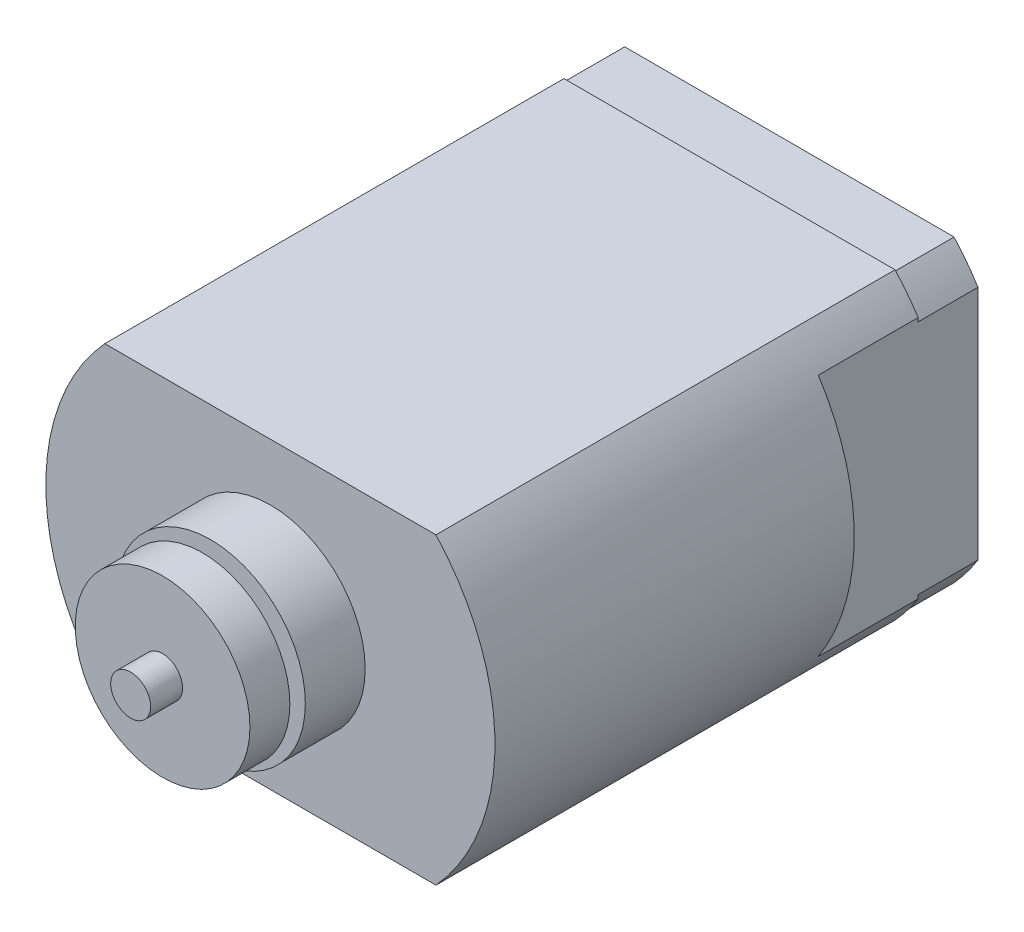
SolidWorks part; units mm, degrees
ref_plane "前视基准面" through (0, 0, 0) normal (0, 0, 1) x (1, 0, 0)
ref_plane "上视基准面" through (0, 0, 0) normal (0, 1, 0) x (1, 0, 0)
ref_plane "右视基准面" through (0, 0, 0) normal (1, 0, 0) x (0, 0, -1)
sketch "草图1" plane through (0, 0, 0) normal (0, 0, 1) x (1, 0, 0)
  line L0 (-11.25, 0) -> (11.25, 0) construction
  line L1 (-8.2947, 7.6) -> (8.2947, 7.6)
  line L2 (-8.2947, -7.6) -> (8.2947, -7.6)
  arc A0 (-8.2947, 7.6) -> (-8.2947, -7.6) centre (0, 0) ccw
  arc A1 (8.2947, -7.6) -> (8.2947, 7.6) centre (0, 0) ccw
  dimension "D1" = 22.5
  dimension "D2" = 15.2
extrude "凸台-拉伸1" add sketch "草图1" along normal blind 26
sketch "草图2" plane through (0, 0, 26) normal (0, 0, 1) x (1, 0, 0)
  circle A0 centre (0, 0) radius 4.75
  dimension "D1" = 9.5
extrude "凸台-拉伸2" add sketch "草图2" along normal blind 3
sketch "草图3" plane through (0, 0, 29) normal (0, 0, 1) x (1, 0, 0)
  circle A0 centre (0, 0) radius 1
  dimension "D1" = 2
extrude "凸台-拉伸3" add sketch "草图3" along normal blind 4
ref_plane "基准面1" through (0, 0, 31.4) normal (0, 0, 1) x (1, 0, 0)
sketch "草图4" plane through (0, 0, 31.4) normal (0, 0, 1) x (1, 0, 0)
  circle A0 centre (0, 0) radius 4.375
  dimension "D1" = 8.75
extrude "T20x0.4" add sketch "草图4" against normal blind 2
sketch "草图5" plane through (0, 0, 0) normal (0, 0, -1) x (-1, 0, 0)
  line L2 (8.2947, -7.6) -> (-8.2947, -7.6) construction
  line L3 (-8.2947, 7.6) -> (8.2947, 7.6) construction
  line L4 (8.2506, 7.5) -> (-8.2506, 7.5)
  line L5 (-8.2506, -7.5) -> (8.2506, -7.5)
  line L6 (8.2506, 7.5) -> (-8.2506, 7.5)
  line L7 (-8.2506, -7.5) -> (8.2506, -7.5)
  line L8 (8.2947, -7.6) -> (-8.2947, -7.6)
  line L9 (-8.2947, 7.6) -> (8.2947, 7.6)
  arc A2 (-8.2947, 7.6) -> (-8.2947, -7.6) centre (0, 0) ccw construction
  arc A3 (8.2947, -7.6) -> (8.2947, 7.6) centre (0, 0) ccw construction
  arc A4 (8.2506, -7.5) -> (8.2506, 7.5) centre (0, 0) ccw
  arc A5 (-8.2506, 7.5) -> (-8.2506, -7.5) centre (0, 0) ccw
  arc A6 (8.2506, -7.5) -> (8.2506, 7.5) centre (0, 0) ccw
  arc A7 (-8.2506, 7.5) -> (-8.2506, -7.5) centre (0, 0) ccw
  arc A8 (-8.2947, 7.6) -> (-8.2947, -7.6) centre (0, 0) ccw
  arc A9 (8.2947, -7.6) -> (8.2947, 7.6) centre (0, 0) ccw
  dimension "D1" = 0.1
extrude "切除-拉伸1" cut sketch "草图5" against normal blind 3
sketch "草图6" plane through (0, 0, 0) normal (0, 0, -1) x (-1, 0, 0)
  circle A0 centre (0, 0) radius 3.135
  dimension "D1" = 6.27
extrude "凸台-拉伸5" add sketch "草图6" along normal blind 2.5
sketch "草图7" plane through (0, 0, -2.5) normal (0, 0, -1) x (-1, 0, 0)
  circle A0 centre (0, 0) radius 1.25
  dimension "D1" = 2.5
extrude "切除-拉伸2" cut sketch "草图7" against normal blind 1
sketch "草图8" plane through (0, 0, 0) normal (0, 0, -1) x (-1, 0, 0)
  line L0 (8.2947, 7.6) -> (-8.2947, 7.6) construction
  line L1 (-9.45, 7.6) -> (-11.25, 7.6)
  line L2 (-9.45, 7.6) -> (-9.45, -7.6)
  line L3 (-9.45, -7.6) -> (-11.25, -7.6)
  line L4 (-11.25, 7.6) -> (-11.25, -7.6)
  line L5 (-9.45, 7.6) -> (-11.25, -7.6) construction
  line L6 (-9.45, -7.6) -> (-11.25, 7.6) construction
  line L7 (-8.2947, -7.6) -> (8.2947, -7.6) construction
  line L8 (11.25, 0) -> (11.25, 7.6) construction
  arc A0 (-8.2947, 7.6) -> (-8.2947, -7.6) centre (0, 0) ccw construction
  arc A1 (8.2947, -7.6) -> (8.2947, 7.6) centre (0, 0) ccw construction
  point P4 (-10.35, 0)
  point P17 (0, 0)
  point P18 (0, 0)
  point P19 (0, 0)
  dimension "D1" = 20.7
extrude "切除-拉伸3" cut sketch "草图8" against normal blind 8
